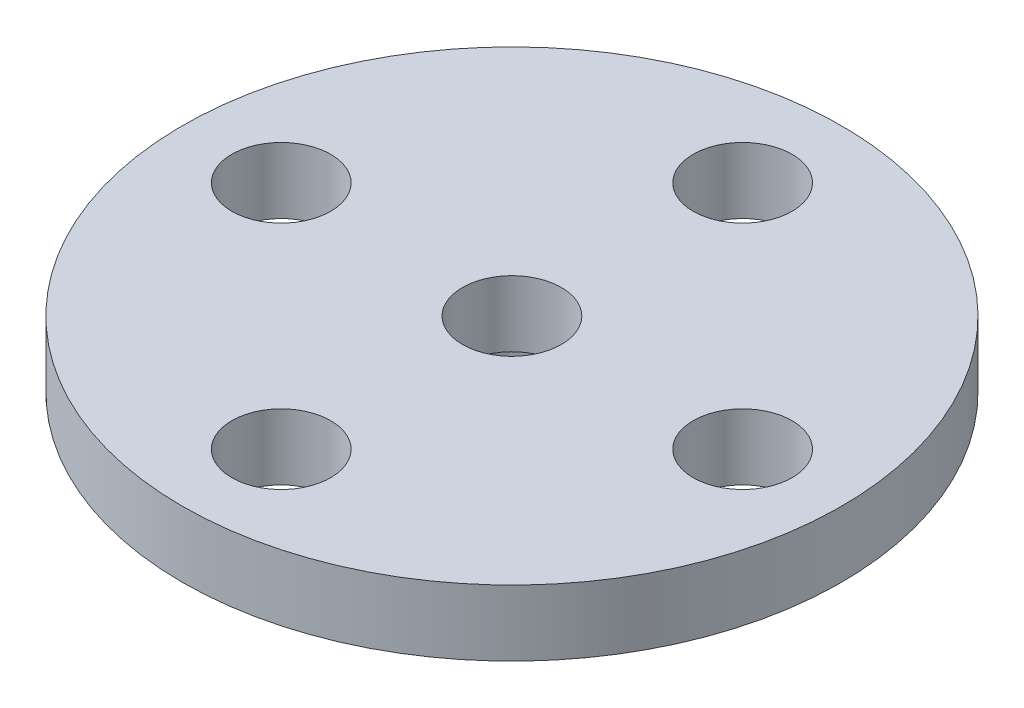
SolidWorks part; units mm, degrees
ref_plane "前视基准面" through (0, 0, 0) normal (0, 0, 1) x (1, 0, 0)
ref_plane "上视基准面" through (0, 0, 0) normal (0, 1, 0) x (1, 0, 0)
ref_plane "右视基准面" through (0, 0, 0) normal (1, 0, 0) x (0, 0, -1)
sketch "草图1" plane through (0, 0, 0) normal (0, 1, 0) x (1, 0, 0)
  line L0 (0, 10) -> (0, -10) construction
  circle A0 centre (0, 0) radius 10
  circle A1 centre (0, 7) radius 1.5
  circle A2 centre (7, 0) radius 1.5
  circle A3 centre (0, -7) radius 1.5
  circle A4 centre (-7, 0) radius 1.5
  circle A5 centre (0, 0) radius 1.5
  circle A6 centre (0, 0) radius 7 construction
  point P16 (0, 0)
  dimension "D1" = 20
  dimension "D2" = 3
  dimension "D4" = 7
  dimension "D3" = 4
extrude "凸台-拉伸1" add sketch "草图1" along normal blind 2
sketch "草图2" plane through (0, 0, 0) normal (0, -1, 0) x (1, 0, 0)
  circle A0 centre (0, 0) radius 3.2032
  circle A1 centre (0, 0) radius 2.0728
extrude "凸台-拉伸2" add sketch "草图2" along normal blind 2.5
